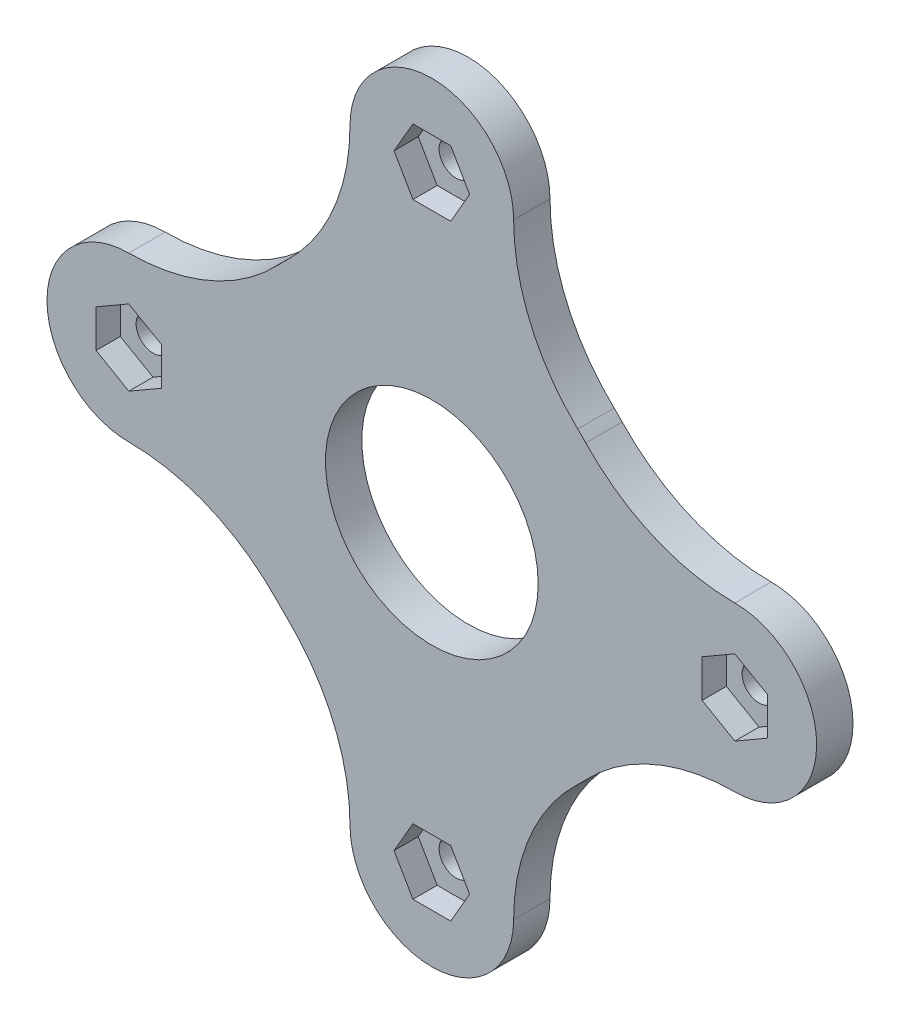
SolidWorks part; units mm, degrees
ref_plane "Front Plane" through (0, 0, 0) normal (0, 0, 1) x (1, 0, 0)
ref_plane "Top Plane" through (0, 0, 0) normal (0, 1, 0) x (1, 0, 0)
ref_plane "Right Plane" through (0, 0, 0) normal (1, 0, 0) x (0, 0, -1)
sketch "Sketch1" plane through (0, 0, 0) normal (0, 0, 1) x (1, 0, 0)
  line L0 (0, -25) -> (0, 25) construction
  line L1 (25, 0) -> (-25, 0) construction
  circle A2 centre (0, 25) radius 1.4
  arc A3 (6.75, 25) -> (-6.75, 25) centre (0, 25) ccw
  circle A4 centre (0, 0) radius 17.5 construction
  arc A5 (-6.75, 25) -> (-12.0384, 12.7015) centre (-23.6948, 25) cw
  arc A6 (6.75, 25) -> (12.0384, 12.7015) centre (23.6948, 25) ccw
  arc A7 (-6.75, 25) -> (6.75, 25) centre (0, 25) ccw construction
  arc A8 (-25, 6.75) -> (-12.7015, 12.0384) centre (-25, 23.6948) ccw
  circle A9 centre (-25, 0) radius 1.4
  arc A10 (-25, 6.75) -> (-25, -6.75) centre (-25, 0) ccw
  arc A11 (-25, -6.75) -> (-12.7015, -12.0384) centre (-25, -23.6948) cw
  arc A12 (-6.75, -25) -> (-12.0384, -12.7015) centre (-23.6948, -25) ccw
  circle A13 centre (0, -25) radius 1.4
  arc A14 (-6.75, -25) -> (6.75, -25) centre (0, -25) ccw
  arc A15 (6.75, -25) -> (12.0384, -12.7015) centre (23.6948, -25) cw
  arc A16 (25, -6.75) -> (12.7015, -12.0384) centre (25, -23.6948) ccw
  circle A17 centre (25, 0) radius 1.4
  arc A18 (25, -6.75) -> (25, 6.75) centre (25, 0) ccw
  arc A19 (25, 6.75) -> (12.7015, 12.0384) centre (25, 23.6948) cw
  arc A20 (-12.7015, 12.0384) -> (-12.0384, 12.7015) centre (0, 0) cw
  arc A21 (12.0384, 12.7015) -> (12.7015, 12.0384) centre (0, 0) cw
  arc A22 (12.7015, -12.0384) -> (12.0384, -12.7015) centre (0, 0) cw
  arc A23 (-12.0384, -12.7015) -> (-12.7015, -12.0384) centre (0, 0) cw
  point P2 (0, 0)
  point P5 (0, 0)
  point P10 (0, 0)
  point P27 (0, 0)
  point P35 (0, 0)
  point P39 (0, 0)
  point P40 (0, 0)
  point P41 (0, 0)
  point P42 (0, 0)
  point P43 (0, 0)
  point P44 (0, 0)
  point P45 (0, 0)
  point P47 (25, 0)
  point P48 (-25, 0)
  dimension "D1" = 35
  dimension "D2" = 13.5
  dimension "D4" = 2.8
  dimension "D3" = 25
extrude "Boss-Extrude1" add sketch "Sketch1" along normal blind 3
sketch "Sketch2" plane through (0, 0, 3) normal (0, 0, 1) x (1, 0, 0)
  line L1 (3.1177, 25) -> (1.5588, 27.7)
  line L2 (1.5588, 27.7) -> (-1.5588, 27.7)
  line L3 (-1.5588, 27.7) -> (-3.1177, 25)
  line L4 (-3.1177, 25) -> (-1.5588, 22.3)
  line L5 (-1.5588, 22.3) -> (1.5588, 22.3)
  line L6 (1.5588, 22.3) -> (3.1177, 25)
  line L7 (25, 3.1177) -> (22.3, 1.5588)
  line L8 (22.3, 1.5588) -> (22.3, -1.5588)
  line L9 (22.3, -1.5588) -> (25, -3.1177)
  line L10 (25, -3.1177) -> (27.7, -1.5588)
  line L11 (27.7, -1.5588) -> (27.7, 1.5588)
  line L12 (27.7, 1.5588) -> (25, 3.1177)
  line L13 (3.1177, -25) -> (1.5588, -22.3)
  line L14 (1.5588, -22.3) -> (-1.5588, -22.3)
  line L15 (-1.5588, -22.3) -> (-3.1177, -25)
  line L16 (-3.1177, -25) -> (-1.5588, -27.7)
  line L17 (-1.5588, -27.7) -> (1.5588, -27.7)
  line L18 (1.5588, -27.7) -> (3.1177, -25)
  line L19 (-25, -3.1177) -> (-22.3, -1.5588)
  line L20 (-22.3, -1.5588) -> (-22.3, 1.5588)
  line L21 (-22.3, 1.5588) -> (-25, 3.1177)
  line L22 (-25, 3.1177) -> (-27.7, 1.5588)
  line L23 (-27.7, 1.5588) -> (-27.7, -1.5588)
  line L24 (-27.7, -1.5588) -> (-25, -3.1177)
  circle A0 centre (0, 25) radius 2.7 construction
  circle A1 centre (25, 0) radius 2.7 construction
  circle A2 centre (0, -25) radius 2.7 construction
  circle A3 centre (-25, 0) radius 2.7 construction
  dimension "D1" = 5.4
extrude "Cut-Extrude1" cut sketch "Sketch2" against normal blind 2
sketch "Sketch3" plane through (0, 0, 3) normal (0, 0, 1) x (1, 0, 0)
  circle A0 centre (0, 0) radius 8.775
  dimension "D1" = 17.55
extrude "Cut-Extrude2" cut sketch "Sketch3" against normal up to next
